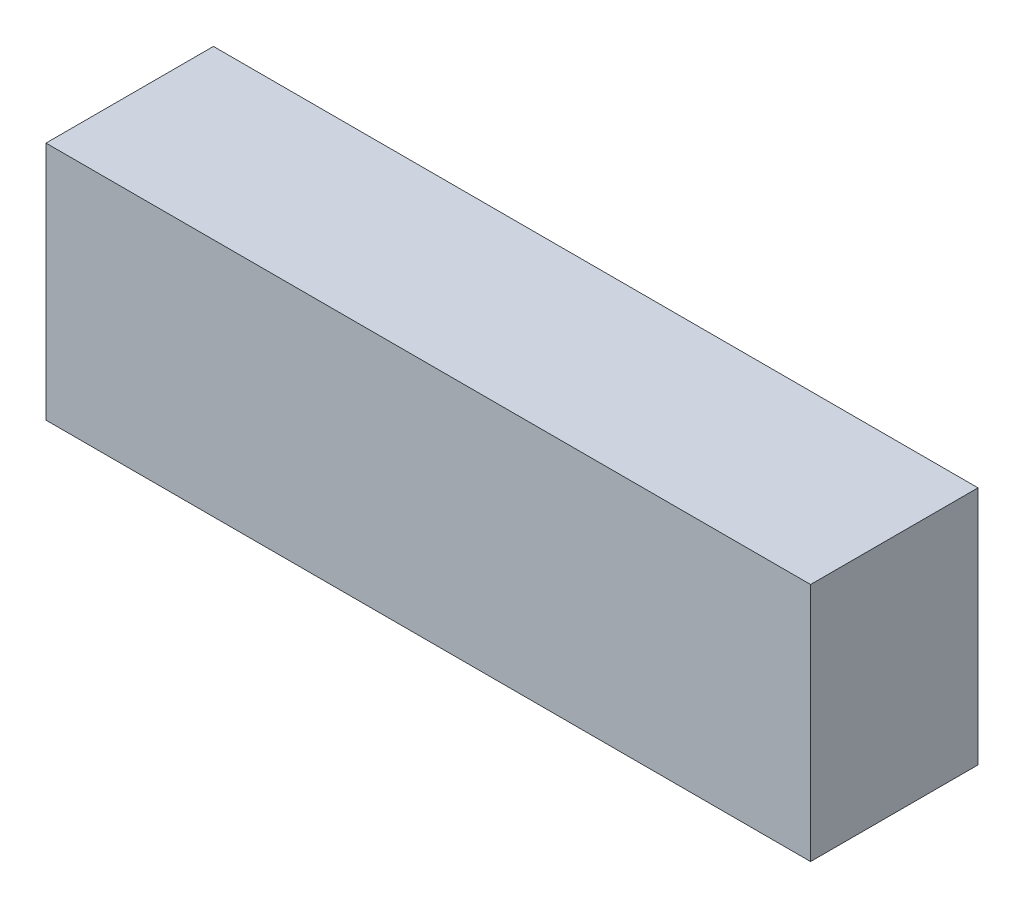
SolidWorks part; units mm, degrees
ref_plane "Plan de face" through (0, 0, 0) normal (0, 0, 1) x (1, 0, 0)
ref_plane "Plan de dessus" through (0, 0, 0) normal (0, 1, 0) x (1, 0, 0)
ref_plane "Plan de droite" through (0, 0, 0) normal (1, 0, 0) x (0, 0, -1)
sketch "Esquisse1" plane through (0, 0, 0) normal (0, 0, 1) x (1, 0, 0)
  line L1 (0, 0) -> (137, 0)
  line L2 (0, 0) -> (0, 43)
  line L3 (0, 43) -> (137, 43)
  line L4 (137, 0) -> (137, 43)
extrude "Boss.-Extru.1" add sketch "Esquisse1" along normal blind 30
